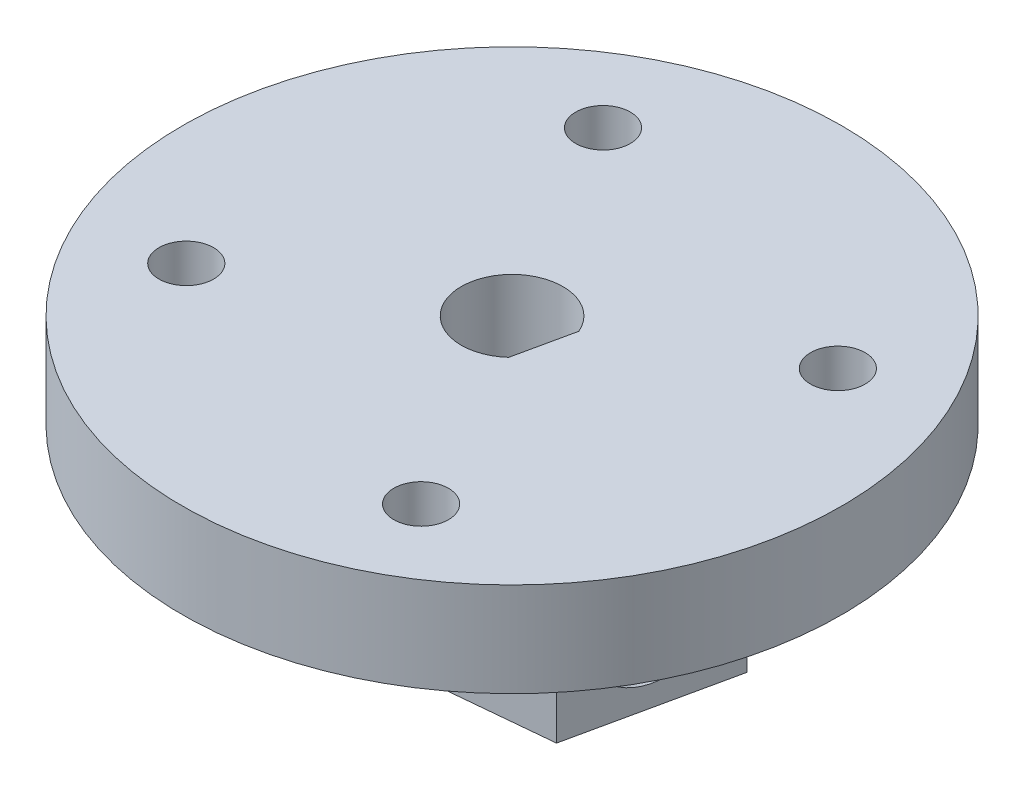
SolidWorks part; units mm, degrees
ref_plane "Front Plane" through (0, 0, 0) normal (0, 0, 1) x (1, 0, 0)
ref_plane "Top Plane" through (0, 0, 0) normal (0, 1, 0) x (1, 0, 0)
ref_plane "Right Plane" through (0, 0, 0) normal (1, 0, 0) x (0, 0, -1)
sketch "Sketch1" plane through (0, 15, 0) normal (0, -1, 0) x (1, 0, 0)
  line L1 (1.8184, 1.9958) -> (2.4817, -1.0636)
  line L21 (-6.2346, -11.0643) -> (6.2346, 11.0643) construction
  line L22 (11.0643, -6.2346) -> (-11.0643, 6.2346) construction
  line L23 (2.4436, -0.8881) -> (1.8565, 1.8203)
  circle A0 centre (6.2346, 11.0643) radius 1.45
  circle A1 centre (-11.0643, 6.2346) radius 1.45
  circle A2 centre (-6.2346, -11.0643) radius 1.45
  circle A3 centre (11.0643, -6.2346) radius 1.45
  arc A5 (2.4817, -1.0636) -> (1.8184, 1.9958) centre (0, 0) cw
  circle A65 centre (0, 0) radius 17.5
extrude "Boss-Extrude1" add sketch "Sketch1" along normal blind 5
sketch "Sketch2" plane through (0, 10, 0) normal (0, -1, 0) x (1, 0, 0)
  line L2 (2.1501, 0.4661) -> (6.0592, 1.3136) construction
  line L14 (6.0592, 1.3136) -> (6.7477, -1.8622)
  line L20 (6.0592, 1.3136) -> (5.3707, 4.4895)
  line L21 (1.8184, 1.9958) -> (2.4817, -1.0636) construction
  line L22 (1.8184, 1.9958) -> (2.4817, -1.0636)
  arc A0 (4.7862, -5.1081) -> (6.7477, -1.8622) centre (0, 0) ccw
  arc A3 (-2.0346, -6.6978) -> (-1.0579, -6.9196) centre (0, 0) ccw
  arc A4 (5.3707, 4.4895) -> (6.7477, -1.8622) centre (0, 0) ccw
  arc A5 (3.8285, -5.8602) -> (4.7862, -5.1081) centre (0, 0) ccw
  arc A6 (5.3707, 4.4895) -> (-2.0346, -6.6978) centre (0, 0) ccw
  arc A7 (1.8184, 1.9958) -> (2.4817, -1.0636) centre (0, 0) ccw construction
  arc A8 (1.8184, 1.9958) -> (2.4817, -1.0636) centre (0, 0) ccw
extrude "Boss-Extrude2" add sketch "Sketch2" along normal up to surface (6.25 mm away)
sketch "Sketch3" plane through (6.0592, 0, 1.3136) normal (0.9773, 0, 0.2119) x (0.2119, 0, -0.9773)
  line L0 (0, 3.75) -> (0, 10)
  line L3 (3.2496, 3.75) -> (-3.2496, 3.75) construction
  line L4 (3.2496, 10) -> (-3.2496, 10) construction
  circle A0 centre (0, 6.875) radius 1.7
  point P3 (0, 3.75)
extrude "Cut-Extrude1" cut sketch "Sketch3" against normal blind 7 contours L0 A0 | L0 A0
sketch "Sketch4" plane through (0, 3.75, 0) normal (0, -1, 0) x (1, 0, 0)
  line L0 (6.0592, 1.3136) -> (2.1501, 0.4661) construction
  line L1 (6.7477, -1.8622) -> (5.3707, 4.4895) construction
  line L3 (4.1046, 0.8899) -> (4.7932, -2.2863) construction
  line L4 (4.7932, -2.2863) -> (3.6205, -2.5406)
  line L5 (3.6205, -2.5406) -> (6.1615, -1.9897)
  line L6 (3.6205, -2.5406) -> (2.2433, 3.8118)
  line L7 (6.1615, -1.9897) -> (4.7843, 4.3627)
  line L8 (2.2433, 3.8118) -> (4.7843, 4.3627)
  line L13 (1.8184, 1.9958) -> (2.4817, -1.0636) construction
  dimension "D1" = 3.25
  dimension "D2" = 3.25
extrude "Cut-Extrude2" cut sketch "Sketch4" against normal blind 5.85 contours L8 L6 L4 L5 L7
sketch "Sketch5" plane through (6.0592, 0, 1.3136) normal (0.9773, 0, 0.2119) x (0.2119, 0, -0.9773)
  line L0 (3.2496, 3.75) -> (3.2496, 10)
  line L1 (3.2496, 3.75) -> (-3.255, 3.75)
  line L2 (3.2496, 10) -> (-3.255, 10)
  line L3 (-3.255, 3.75) -> (-3.255, 10)
  circle A0 centre (0, 6.875) radius 1.7 construction
  circle A1 centre (0, 6.875) radius 1.7
extrude "Boss-Extrude3" add sketch "Sketch5" along normal blind 2
sketch "Sketch6" plane through (8.0138, 0, 1.7374) normal (0.9773, 0, 0.2119) x (0.2119, 0, -0.9773)
  circle A0 centre (0, 6.875) radius 3
extrude "Cut-Extrude3" cut sketch "Sketch6" against normal blind 1.5
sketch "Sketch7" plane through (8.0138, 0, 1.7374) normal (0.9773, 0, 0.2119) x (0.2119, 0, -0.9773)
  line L0 (3.2496, 10) -> (3.2496, 3.75)
  line L1 (3.2496, 10) -> (-3.2585, 10)
  line L2 (3.2496, 3.75) -> (-3.2585, 3.75)
  line L3 (-3.2585, 10) -> (-3.2585, 3.75)
  circle A0 centre (0, 6.875) radius 3 construction
  circle A1 centre (0, 6.875) radius 3
extrude "Boss-Extrude4" add sketch "Sketch7" along normal blind 1.5
sketch "Sketch8" plane through (0, 3.75, 0) normal (0, -1, 0) x (1, 0, 0)
  line L0 (8.5775, 6.217) -> (0.6996, 6.965)
  line L1 (10.3802, -2.098) -> (3.534, -6.0424)
  line L2 (10.1683, -1.1207) -> (10.3802, -2.098)
  line L3 (8.7894, 5.2397) -> (8.5775, 6.217)
  line L6 (6.7477, -1.8622) -> (10.1683, -1.1207)
  line L7 (10.1683, -1.1207) -> (8.7894, 5.2397)
  line L8 (8.7894, 5.2397) -> (7.3234, 4.9219)
  line L9 (7.3234, 4.9219) -> (7.3242, 4.9184)
  line L10 (7.3242, 4.9184) -> (5.3696, 4.4947)
  line L11 (5.3696, 4.4947) -> (5.3707, 4.4895)
  line L13 (10.1683, -1.1207) -> (8.7894, 5.2397)
  line L18 (4.7843, 4.3627) -> (2.2433, 3.8118)
  line L19 (2.2433, 3.8118) -> (3.6205, -2.5406)
  line L20 (3.6205, -2.5406) -> (6.1615, -1.9897)
  line L21 (6.1615, -1.9897) -> (4.7843, 4.3627)
  line L22 (4.7843, 4.3627) -> (2.2433, 3.8118)
  line L24 (3.6205, -2.5406) -> (6.1615, -1.9897)
  line L25 (6.1615, -1.9897) -> (4.7843, 4.3627)
  arc A0 (5.3707, 4.4895) -> (6.7477, -1.8622) centre (0, 0) ccw construction
  arc A1 (5.3707, 4.4895) -> (6.7477, -1.8622) centre (0, 0) ccw
  arc A3 (0.6996, 6.965) -> (3.534, -6.0424) centre (0, 0) ccw
  dimension "D1" = 0
  dimension "D2" = 0
extrude "Boss-Extrude5" add sketch "Sketch8" against normal up to surface (6.25 mm away) up to face at (0, 10, -17.5)
sketch "Sketch10" plane through (0, 3.75, 0) normal (0, -1, 0) x (1, 0, 0)
  line L3 (1.8184, 1.9958) -> (2.4817, -1.0636) construction
  line L5 (3.6205, -2.5406) -> (2.2433, 3.8118) construction
  line L6 (8.5775, 6.217) -> (0.6996, 6.965)
  line L7 (3.534, -6.0424) -> (10.3802, -2.098)
  line L8 (10.3802, -2.098) -> (8.5775, 6.217)
  line L9 (8.5775, 6.217) -> (0.6996, 6.965)
  line L10 (3.534, -6.0424) -> (10.3802, -2.098)
  line L11 (10.3802, -2.098) -> (8.5775, 6.217)
  line L12 (6.1615, -1.9897) -> (4.7843, 4.3627) construction
  line L14 (6.1615, -1.9897) -> (3.6205, -2.5406) construction
  line L15 (2.2433, 3.8118) -> (4.7843, 4.3627) construction
  line L16 (6.1615, -1.9897) -> (3.6205, -2.5406)
  line L17 (6.1615, -1.9897) -> (4.7843, 4.3627)
  line L18 (3.6205, -2.5406) -> (2.2433, 3.8118)
  line L19 (2.2433, 3.8118) -> (4.7843, 4.3627)
  line L20 (1.8184, 1.9958) -> (2.4817, -1.0636)
  arc A1 (1.8184, 1.9958) -> (2.4817, -1.0636) centre (0, 0) ccw construction
  arc A2 (0.6996, 6.965) -> (3.534, -6.0424) centre (0, 0) ccw
  arc A3 (0.6996, 6.965) -> (3.534, -6.0424) centre (0, 0) ccw
  arc A4 (1.8184, 1.9958) -> (2.4817, -1.0636) centre (0, 0) ccw
  dimension "D1" = 0
extrude "Boss-Extrude6" add sketch "Sketch10" along normal blind 1
